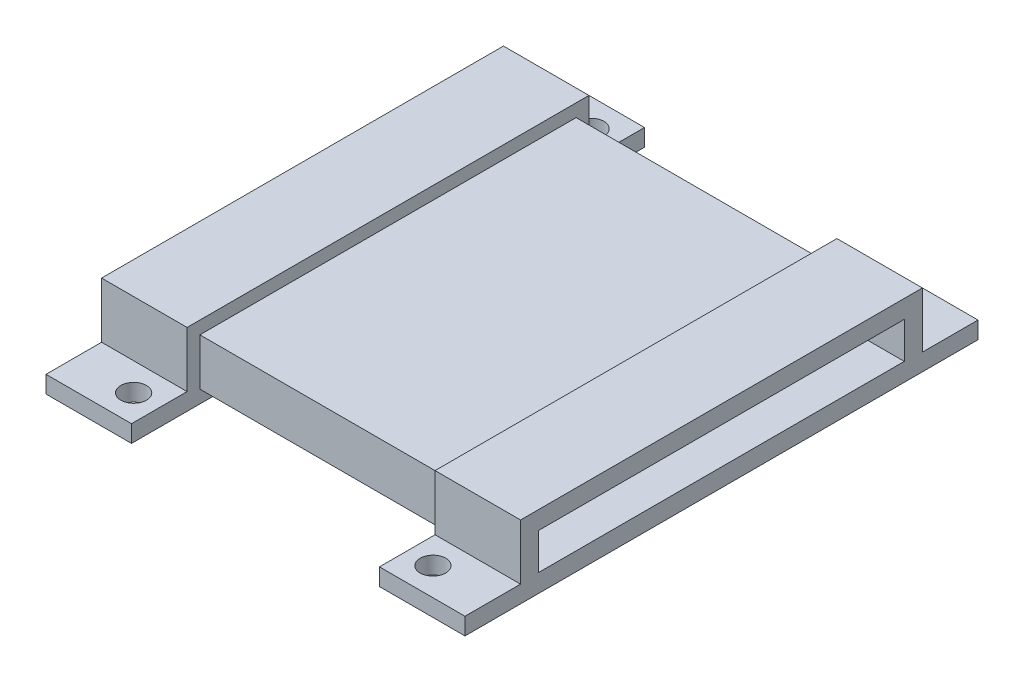
SolidWorks part; units mm, degrees
material "ABS PC"
ref_plane "Front Plane" through (0, 0, 0) normal (0, 0, 1) x (1, 0, 0)
ref_plane "Top Plane" through (0, 0, 0) normal (0, 1, 0) x (1, 0, 0)
ref_plane "Right Plane" through (0, 0, 0) normal (1, 0, 0) x (0, 0, -1)
sketch "Sketch1" plane through (0, 0, 0) normal (0, 1, 0) x (1, 0, 0)
  line L1 (-52.356, -25.5021) -> (-3.356, -25.5021)
  line L2 (-52.356, -25.5021) -> (-52.356, 34.4979)
  line L3 (-52.356, 34.4979) -> (-3.356, 34.4979)
  line L4 (-3.356, -25.5021) -> (-3.356, 34.4979)
  dimension "D1" = 60
  dimension "D2" = 49
extrude "Boss-Extrude1" add sketch "Sketch1" along normal blind 15
sketch "Sketch2" plane through (0, 15, 0) normal (0, 1, 0) x (-1, 0, 0)
  line L0 (45.356, -34.1012) -> (45.356, 25.5021) construction
  line L1 (52.356, 25.5021) -> (3.356, 25.5021) construction
  line L2 (10.356, -34.4979) -> (10.356, 25.5021) construction
  line L3 (3.356, -34.4979) -> (52.356, -34.4979) construction
  line L4 (45.356, -31.2479) -> (10.356, -31.2479) construction
  line L5 (45.356, 22.2521) -> (10.356, 22.2521) construction
  line L6 (45.356, -31.2479) -> (52.356, -31.2479) construction
  line L7 (52.356, -34.4979) -> (52.356, 25.5021) construction
  line L8 (10.356, -31.2479) -> (3.356, -31.2479) construction
  line L9 (3.356, 25.5021) -> (3.356, -34.4979) construction
  line L10 (27.856, -34.4979) -> (27.856, -31.2479) construction
  line L11 (27.856, -31.2479) -> (27.856, 22.2521) construction
  line L12 (27.856, 22.2521) -> (27.856, 25.5021) construction
  circle A0 centre (45.356, -31.2479) radius 1.5
  circle A1 centre (10.356, -31.2479) radius 1.5
  circle A2 centre (10.356, 22.2521) radius 1.5
  circle A3 centre (45.356, 22.2521) radius 1.5
  dimension "D3" = 3
  dimension "D1" = 35
  dimension "D2" = 53.5
sketch "Sketch5" plane through (-52.356, 0, 0) normal (-1, 0, 0) x (0, 0, 1)
  line L1 (-34.4979, 15) -> (-27.9979, 15)
  line L2 (-34.4979, 15) -> (-34.4979, 2)
  line L3 (-34.4979, 2) -> (-27.9979, 2)
  line L4 (-27.9979, 15) -> (-27.9979, 2)
  dimension "D1" = 6.5
  dimension "D2" = 13
extrude "Cut-Extrude2" cut sketch "Sketch5" against normal blind 54
extrude "Cut-Extrude3" cut sketch "Sketch2" against normal blind 54 contours A3 | A2 | A0 | A1
sketch "Sketch7" plane through (-52.356, 0, 0) normal (-1, 0, 0) x (0, 0, 1)
  line L1 (25.5021, 15) -> (19.0021, 15)
  line L2 (25.5021, 15) -> (25.5021, 2)
  line L3 (25.5021, 2) -> (19.0021, 2)
  line L4 (19.0021, 15) -> (19.0021, 2)
  dimension "D1" = 6.5
  dimension "D2" = 13
extrude "Cut-Extrude4" cut sketch "Sketch7" against normal blind 54
sketch "Sketch8" plane through (0, 0, 19.0021) normal (0, 0, 1) x (1, 0, 0)
  line L1 (-3.356, 15) -> (-3.356, 2) construction
  line L2 (-52.356, 15) -> (-52.356, 2) construction
  line L3 (-42.356, 8.5) -> (-52.356, 8.5) construction
  line L4 (-52.356, 8.5) -> (-42.356, 8.5) construction
  line L5 (-42.356, 8.5) -> (-13.356, 8.5) construction
  line L6 (-13.356, 8.5) -> (-3.356, 8.5) construction
  line L7 (-42.356, 8.5) -> (-13.356, 8.5)
  line L8 (-42.356, 8.5) -> (-42.356, 7)
  line L9 (-42.356, 7) -> (-13.356, 7)
  line L10 (-13.356, 8.5) -> (-13.356, 7)
  line L11 (-52.356, 8.5) -> (-3.356, 8.5)
  line L12 (-52.356, 8.5) -> (-52.356, 15)
  line L13 (-52.356, 15) -> (-3.356, 15)
  line L14 (-3.356, 8.5) -> (-3.356, 15)
  line M1 (-3.356, 15) -> (-52.356, 15)
  line M2 (-52.356, 15) -> (-52.356, 2)
  line M4 (-3.356, 2) -> (-3.356, 15)
  dimension "D1" = 10
  dimension "D2" = 1.5
extrude "Cut-Extrude5" cut sketch "Sketch8" against normal blind 54 contours L11 L7 M2 M4 M1 | L10 L7 L8 L9
sketch "Sketch9" plane through (0, 7, 0) normal (0, 1, 0) x (-1, 0, 0)
  line L0 (42.356, -27.9979) -> (42.356, 19.0021) construction
  line L1 (13.356, -27.9979) -> (42.356, -27.9979)
  line L2 (13.356, -27.9979) -> (13.356, -26.4979)
  line L3 (13.356, -26.4979) -> (42.356, -26.4979)
  line L4 (42.356, -27.9979) -> (42.356, -26.4979)
  dimension "D1" = 1.5
extrude "Cut-Extrude6" cut sketch "Sketch9" against normal blind 54
sketch "Sketch14" plane through (0, 0, -26.4979) normal (0, 0, -1) x (-1, 0, 0)
  line L0 (42.356, 0) -> (42.356, 7) construction
  line L1 (42.356, 0) -> (13.356, 0)
  line L2 (42.356, 0) -> (42.356, 1.5)
  line L3 (42.356, 1.5) -> (13.356, 1.5)
  line L4 (13.356, 0) -> (13.356, 1.5)
  line L5 (13.356, 0) -> (13.356, 7) construction
  dimension "D1" = 1.5
extrude "Cut-Extrude7" cut sketch "Sketch14" along normal blind 17 and the other way blind 76
sketch "Sketch16" plane through (0, 7, 0) normal (0, 1, 0) x (-1, 0, 0)
  line L0 (13.356, -26.4979) -> (13.356, 19.0021) construction
  line L1 (42.356, 19.0021) -> (13.356, 19.0021)
  line L2 (42.356, 19.0021) -> (42.356, 17.5021)
  line L3 (42.356, 17.5021) -> (13.356, 17.5021)
  line L4 (13.356, 19.0021) -> (13.356, 17.5021)
  dimension "D1" = 1.5
extrude "Cut-Extrude8" cut sketch "Sketch16" against normal blind 17
sketch "Sketch17" plane through (0, 0, 25.5021) normal (0, 0, 1) x (1, 0, 0)
  line L0 (-3.356, 2) -> (-52.356, 2) construction
  line L1 (-42.356, 1.5) -> (-13.356, 1.5)
  line L2 (-42.356, 1.5) -> (-42.356, 2)
  line L3 (-42.356, 2) -> (-13.356, 2)
  line L4 (-13.356, 1.5) -> (-13.356, 2)
  line L5 (-13.356, 1.5) -> (-13.356, 7) construction
extrude "Cut-Extrude9" cut sketch "Sketch17" against normal blind 7
sketch "Sketch18" plane through (0, 0, -34.4979) normal (0, 0, -1) x (-1, 0, 0)
  line L0 (3.356, 2) -> (52.356, 2) construction
  line L1 (13.356, 1.5) -> (42.356, 1.5)
  line L2 (13.356, 1.5) -> (13.356, 2)
  line L3 (13.356, 2) -> (42.356, 2)
  line L4 (42.356, 1.5) -> (42.356, 2)
  dimension "D1" = 29
extrude "Cut-Extrude10" cut sketch "Sketch18" against normal blind 7
sketch "Sketch19" plane through (-52.356, 0, 0) normal (-1, 0, 0) x (0, 0, 1)
  line L0 (19.0021, 8.5) -> (16.8808, 6.3787) construction
  line L1 (-27.9979, 8.5) -> (-27.9979, 0) construction
  line L2 (-34.4979, 0) -> (25.5021, 0) construction
  line L3 (-27.9979, 0) -> (-25.8766, 2.1213) construction
  line L4 (-27.9979, 8.5) -> (-25.8766, 6.3787) construction
  line L5 (19.0021, 8.5) -> (19.0021, 0) construction
  line L6 (19.0021, 0) -> (16.8808, 2.1213) construction
  line L8 (-25.8766, 6.3787) -> (16.8808, 6.3787)
  line L9 (-25.8766, 6.3787) -> (-25.8766, 2.1213)
  line L10 (-25.8766, 2.1213) -> (16.8808, 2.1213)
  line L11 (16.8808, 6.3787) -> (16.8808, 2.1213)
  dimension "D1" = 3
extrude "Cut-Extrude12" cut sketch "Sketch19" against normal blind 51
